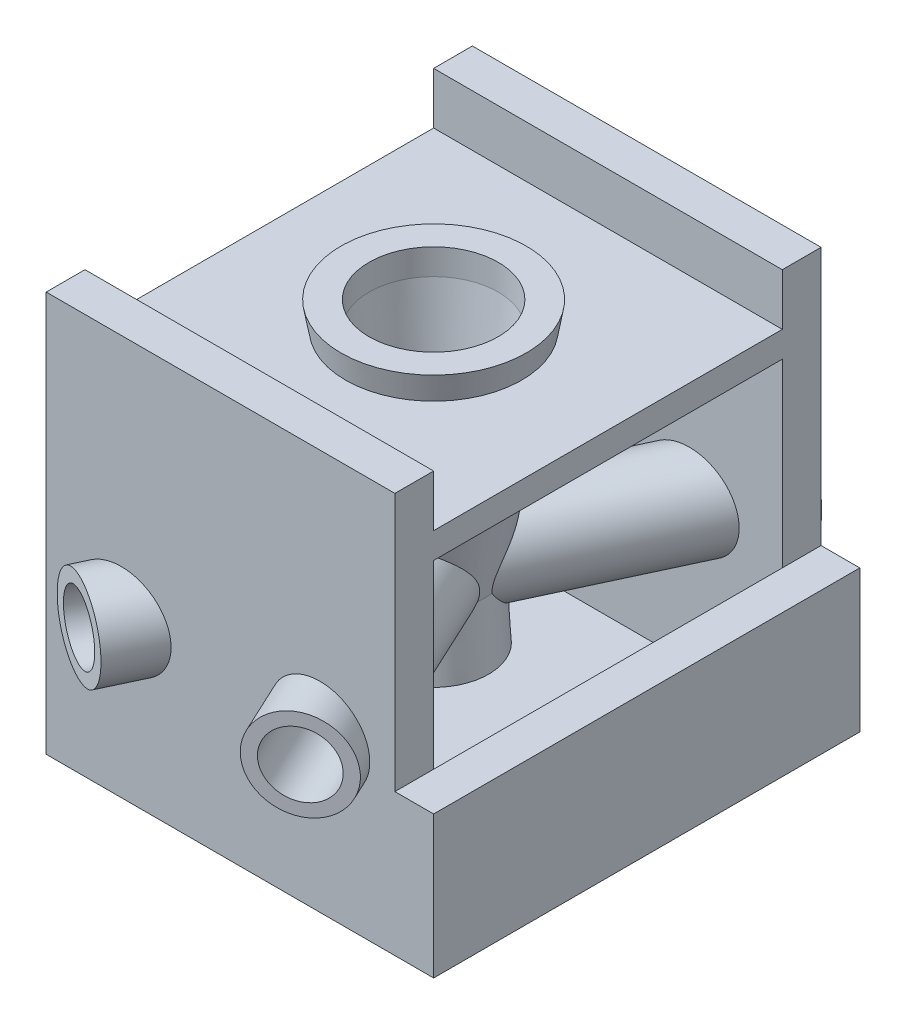
SolidWorks part; units mm, degrees
ref_plane "Front Plane" through (0, 0, 0) normal (0, 0, 1) x (1, 0, 0)
ref_plane "Top Plane" through (0, 0, 0) normal (0, 1, 0) x (1, 0, 0)
ref_plane "Right Plane" through (0, 0, 0) normal (1, 0, 0) x (0, 0, -1)
sketch "Sketch1" plane through (0, 0, 0) normal (0, 1, 0) x (1, 0, 0)
  line L0 (-16.5, 16.5) -> (16.5, 16.5)
  line L1 (-13.5, 13.5) -> (13.5, 13.5)
  line L2 (-13.5, 13.5) -> (-13.5, -13.5)
  line L3 (-13.5, -13.5) -> (13.5, -13.5)
  line L4 (13.5, 13.5) -> (13.5, -13.5)
  line L5 (-13.5, 13.5) -> (13.5, -13.5) construction
  line L6 (-13.5, -13.5) -> (13.5, 13.5) construction
  line L7 (16.5, 16.5) -> (16.5, -16.5)
  line L8 (-16.5, -16.5) -> (16.5, -16.5)
  line L9 (-16.5, 16.5) -> (-16.5, -16.5)
  point P0 (0, 0)
  dimension "D1" = 27
  dimension "D2" = 27
  dimension "D3" = 3
extrude "Boss-Extrude1" add sketch "Sketch1" along normal blind 30
sketch "Sketch3" plane through (-13.5, 0, 0) normal (1, 0, 0) x (0, 0, -1)
  line L1 (-13.5, 0) -> (13.5, 0)
  line L2 (-13.5, 0) -> (-13.5, 30)
  line L3 (-13.5, 30) -> (13.5, 30)
  line L4 (13.5, 0) -> (13.5, 30)
extrude "Cut-Extrude1" cut sketch "Sketch3" against normal blind 30
sketch "Sketch4" plane through (16.5, 0, 0) normal (1, 0, 0) x (0, 0, -1)
  line L1 (-16.5, 0) -> (16.5, 0)
  line L2 (-16.5, 0) -> (-16.5, -1)
  line L3 (-16.5, -1) -> (16.5, -1)
  line L4 (16.5, 0) -> (16.5, -1)
extrude "Boss-Extrude2" add sketch "Sketch4" against normal up to vertex (33 mm away)
sketch "Sketch5" plane through (13.5, 0, 0) normal (-1, 0, 0) x (0, 0, 1)
  line L0 (-13.5, 0) -> (-13.5, 24.4707)
  line L1 (-13.5, 30) -> (-13.5, 0) construction
  line L2 (13.5, 30) -> (13.5, 0) construction
  line L3 (-13.5, 24.4707) -> (13.5, 24.4707)
  line L4 (-13.5, 24.4707) -> (-13.5, 22.4707)
  line L5 (-13.5, 22.4707) -> (13.5, 22.4707)
  line L6 (13.5, 24.4707) -> (13.5, 22.4707)
sketch "Sketch7" plane through (0, 0, 0) normal (0, 1, 0) x (1, 0, 0)
  line L0 (13.5, 13.5) -> (9.5, 13.5)
  line L1 (13.5, 13.5) -> (-16.5, 13.5) construction
  line L2 (9.5, 13.5) -> (13.5, 9.5)
  line L3 (13.5, -13.5) -> (13.5, 13.5) construction
  line L4 (13.5, 9.5) -> (13.5, 13.5)
extrude "Boss-Extrude4" add sketch "Sketch7" along normal blind 4.8
sketch "Sketch8" plane through (0, 0, 0) normal (0, 1, 0) x (1, 0, 0)
  line L0 (13.5, 9.5) -> (9.5, 13.5)
  line L1 (9.5, 13.5) -> (13.5, 13.5)
  line L2 (13.5, 13.5) -> (13.5, 9.5)
extrude "Cut-Extrude3" cut sketch "Sketch8" along normal blind 2.8
sketch "Sketch9" plane through (0, 0, 0) normal (0, 1, 0) x (1, 0, 0)
  line L0 (13.5, -13.5) -> (13.5, -9.5)
  line L1 (13.5, -13.5) -> (13.5, 13.5) construction
  line L2 (13.5, -9.5) -> (9.5, -13.5)
  line L3 (-16.5, -13.5) -> (13.5, -13.5) construction
  line L4 (9.5, -13.5) -> (13.5, -13.5)
extrude "Boss-Extrude5" add sketch "Sketch9" along normal blind 4.8
sketch "Sketch10" plane through (0, 0, 0) normal (0, 1, 0) x (1, 0, 0)
  line L0 (9.5, -13.5) -> (13.5, -9.5)
  line L1 (13.5, -9.5) -> (13.5, -13.5)
  line L2 (13.5, -13.5) -> (9.5, -13.5)
extrude "Cut-Extrude5" cut sketch "Sketch10" along normal blind 2.8
sketch "Sketch12" plane through (0, 0, 0) normal (0, 1, 0) x (1, 0, 0)
  line L1 (13.5, 13.5) -> (-16.5, 13.5)
  line L2 (13.5, 13.5) -> (13.5, -13.5)
  line L3 (13.5, -13.5) -> (-16.5, -13.5)
  line L4 (-16.5, 13.5) -> (-16.5, -13.5)
  line L5 (-16.5, -13.5) -> (-13.5, -13.5)
  line L6 (-16.5, -13.5) -> (-16.5, 13.5)
  line L7 (-16.5, 13.5) -> (-13.5, 13.5)
  line L8 (-13.5, -13.5) -> (-13.5, 13.5)
  line M2 (-16.5, -13.5) -> (13.5, -13.5)
  line M5 (-16.5, 13.5) -> (-16.5, -13.5)
extrude "Cut-Extrude6" cut sketch "Sketch12" against normal blind 10 contours L8 L1 M2 M5
sketch "Sketch13" plane through (0, -1, 0) normal (0, -1, 0) x (1, 0, 0)
  line L1 (-16.5, 16.5) -> (-13.5, 16.5)
  line L2 (-16.5, 16.5) -> (-16.5, -20.8947)
  line L3 (-16.5, -20.8947) -> (-13.5, -20.8947)
  line L4 (-13.5, 16.5) -> (-13.5, -20.8947)
extrude "Cut-Extrude7" cut sketch "Sketch13" against normal through all
ref_plane "Plane1" through (0, 10, 0) normal (0, 1, 0) x (1, 0, 0)
sketch "Sketch26" plane through (13.5, 0, 0) normal (-1, 0, 0) x (0, 0, 1)
  line L0 (0, 0) -> (0, 25)
  line L1 (13.5, 0) -> (-13.5, 0) construction
  line L2 (13.5, 30) -> (13.5, 4.8) construction
  line L3 (-13.5, 26) -> (13.5, 26)
  line L4 (-13.5, 26) -> (-13.5, 24)
  line L5 (-13.5, 24) -> (13.5, 24)
  line L6 (13.5, 26) -> (13.5, 24)
  line L7 (-13.5, 26) -> (13.5, 24) construction
  line L8 (-13.5, 24) -> (13.5, 26) construction
extrude "Boss-Extrude8" add sketch "Sketch26" along direction (1, 0, 0) on the side of the normal through all
sketch "Sketch29" plane through (0, 26, 0) normal (0, 1, 0) x (1, 0, 0)
  line L0 (0, 0) -> (0, 19.9103) construction
  line L1 (0, 0) -> (-10.1096, 21.6801) construction
  line L2 (0, 0) -> (12.6785, 27.1892) construction
ref_plane "Plane2" through (0, 0, 0) normal (0.9063, 0, 0.4226) x (0.4226, 0, -0.9063)
ref_plane "Plane3" through (0, 0, 0) normal (0.9063, 0, -0.4226) x (-0.4226, 0, -0.9063)
ref_plane "Plane4" through (-8.7311, 0, 18.7238) normal (-0.4226, 0, 0.9063) x (0, -1, 0)
sketch "Sketch30" plane through (-8.7311, 0, 18.7238) normal (-0.4226, 0, 0.9063) x (0, -1, 0)
  line L0 (0, 0) -> (-11, 0)
  circle A0 centre (-11, 0) radius 2.5
  circle A1 centre (-11, 0) radius 3.5
  dimension "D1" = 1
extrude "Boss-Extrude15" add sketch "Sketch30" against normal blind 42 separate body
ref_plane "Plane5" through (-8.7311, 0, -18.7238) normal (-0.4226, 0, -0.9063) x (0, 1, 0)
sketch "Sketch31" plane through (-8.7311, 0, -18.7238) normal (-0.4226, 0, -0.9063) x (0, 1, 0)
  line L0 (0, 0) -> (11, 0)
  circle A0 centre (11, 0) radius 2.5
  circle A1 centre (11, 0) radius 3.5
  dimension "D1" = 1
extrude "Boss-Extrude16" add sketch "Sketch31" against normal blind 42
sketch "Sketch38" plane through (0, 10, 0) normal (0, 1, 0) x (1, 0, 0)
  circle A0 centre (0, 0) radius 4
extrude "Boss-Extrude17" add sketch "Sketch38" against normal blind 5 draft 3 and the other way blind 18 draft 10 other way draft outward yes draft outward yes
sketch "Sketch37" plane through (-8.7311, 0, -18.7238) normal (-0.4226, 0, -0.9063) x (0, 1, 0)
  circle A0 centre (11, 0) radius 2.5
extrude "Cut-Extrude14" cut sketch "Sketch37" against normal through all
sketch "Sketch36" plane through (-8.7311, 0, 18.7238) normal (-0.4226, 0, 0.9063) x (0, -1, 0)
  circle A0 centre (-11, 0) radius 2.5
extrude "Cut-Extrude13" cut sketch "Sketch36" against normal through all
sketch "Sketch39" plane through (0, 10, 0) normal (0, 1, 0) x (1, 0, 0)
  circle A0 centre (0, 0) radius 2
extrude "Cut-Extrude15" cut sketch "Sketch39" against normal blind 6 draft 4 and the other way blind 6 draft 4
ref_plane "Plane6" through (0, 14.5, 0) normal (0, 1, 0) x (1, 0, 0)
sketch "Sketch27" plane through (0, 26, 0) normal (0, 1, 0) x (1, 0, 0)
  line L0 (-13.5, 13.5) -> (13.5, -13.5)
  line L1 (13.5, 13.5) -> (13.5, -13.5) construction
  circle A0 centre (0, 0) radius 5
extrude "Cut-Extrude12" cut sketch "Sketch27" against normal blind 16 draft 8 and the other way blind 5 contours L0 A0 | L0 A0
sketch "Sketch40" plane through (0, 30, 0) normal (0, 1, 0) x (1, 0, 0)
  line L0 (13.5, 13.5) -> (13.5, 18.4223)
  line L1 (13.5, 18.4223) -> (20.5582, 18.4223)
  line L2 (20.5582, 18.4223) -> (20.5582, -21.1806)
  line L3 (20.5582, -21.1806) -> (13.5, -21.1806)
  line L4 (13.5, -21.1806) -> (13.5, -13.5)
  line L5 (13.5, -13.5) -> (13.5, 13.5)
extrude "Cut-Extrude16" cut sketch "Sketch40" against normal blind 20
